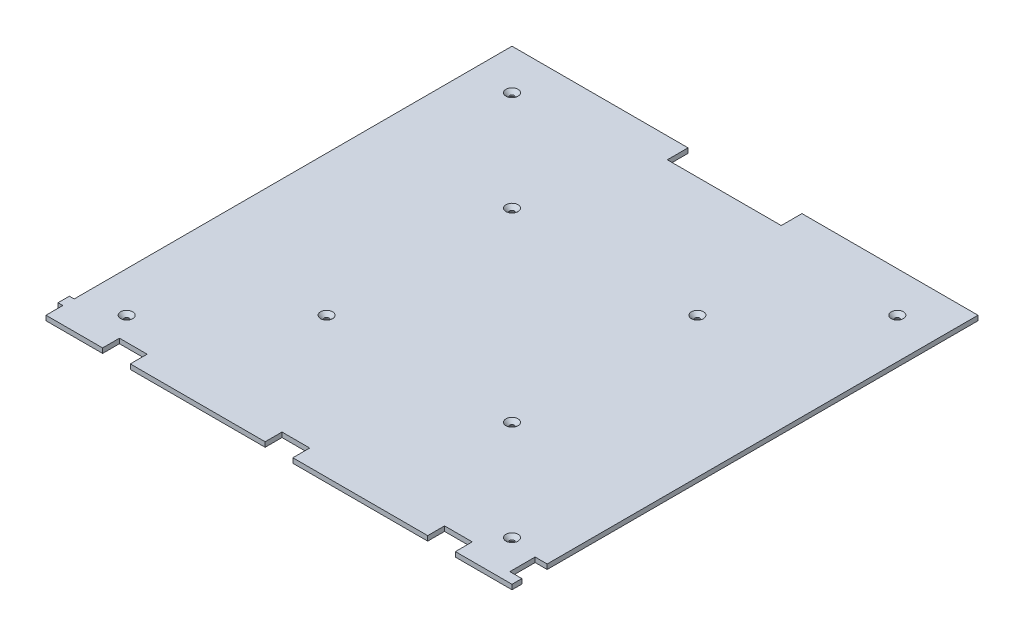
SolidWorks part; units mm, degrees
ref_plane "Front Plane" through (0, 0, 0) normal (0, 0, 1) x (1, 0, 0)
ref_plane "Top Plane" through (0, 0, 0) normal (0, 1, 0) x (1, 0, 0)
ref_plane "Right Plane" through (0, 0, 0) normal (1, 0, 0) x (0, 0, -1)
sketch "Sketch1" plane through (0, 0, 0) normal (0, 1, 0) x (1, 0, 0)
  line L0 (5.5, -97) -> (61.9965, -97) construction
  line L1 (5.5, -90.0036) -> (5.5, -97) construction
  line L2 (-5.5, -90.0036) -> (5.5, -90.0036) construction
  line L3 (-5.5, -97) -> (-5.5, -90.0036) construction
  line L4 (-61.9965, -97) -> (-5.5, -97) construction
  line L5 (-61.9965, -90.0036) -> (-61.9965, -97) construction
  line L6 (-72.9965, -90.0036) -> (-61.9965, -90.0036) construction
  line L7 (-72.9965, -97) -> (-72.9965, -90.0036) construction
  line L8 (-97, -97) -> (-72.9965, -97) construction
  line L9 (-97, -90) -> (-97, -97) construction
  line L10 (-99, -90) -> (-97, -90) construction
  line L11 (-99, -84.8) -> (-99, -90) construction
  line L12 (-97, -84.8) -> (-99, -84.8) construction
  line L13 (-97, 97) -> (-97, -84.8) construction
  line L14 (-23.4, 97) -> (-97, 97) construction
  line L15 (-23.4, 88.4) -> (-23.4, 97) construction
  line L16 (23.4, 88.4) -> (-23.4, 88.4) construction
  line L17 (23.4, 97) -> (23.4, 88.4) construction
  line L18 (97, 97) -> (23.4, 97) construction
  line L19 (97, -82.4) -> (97, 97) construction
  line L20 (92, -82.4) -> (97, -82.4) construction
  line L21 (92, -92.4) -> (92, -82.4) construction
  line L22 (97, -92.4) -> (92, -92.4) construction
  line L23 (97, -97) -> (97, -92.4) construction
  line L24 (72.9965, -97) -> (97, -97) construction
  line L25 (72.9965, -90.0036) -> (72.9965, -97) construction
  line L26 (61.9965, -90.0036) -> (72.9965, -90.0036) construction
  line L27 (61.9965, -97) -> (61.9965, -90.0036) construction
  line L28 (5.75, -96.75) -> (61.7465, -96.75)
  line L29 (61.7465, -96.75) -> (61.7465, -89.7536)
  line L30 (61.7465, -89.7536) -> (73.2465, -89.7536)
  line L31 (73.2465, -89.7536) -> (73.2465, -96.75)
  line L32 (73.2465, -96.75) -> (96.75, -96.75)
  line L33 (96.75, -96.75) -> (96.75, -92.65)
  line L34 (96.75, -92.65) -> (91.75, -92.65)
  line L35 (91.75, -92.65) -> (91.75, -82.15)
  line L36 (91.75, -82.15) -> (96.75, -82.15)
  line L37 (96.75, -82.15) -> (96.75, 96.75)
  line L38 (96.75, 96.75) -> (23.65, 96.75)
  line L39 (23.65, 96.75) -> (23.65, 88.15)
  line L40 (23.65, 88.15) -> (-23.65, 88.15)
  line L41 (-23.65, 88.15) -> (-23.65, 96.75)
  line L42 (-23.65, 96.75) -> (-96.75, 96.75)
  line L43 (-96.75, 96.75) -> (-96.75, -85.05)
  line L44 (-96.75, -85.05) -> (-98.75, -85.05)
  line L45 (-98.75, -85.05) -> (-98.75, -89.75)
  line L46 (-98.75, -89.75) -> (-96.75, -89.75)
  line L47 (-96.75, -89.75) -> (-96.75, -96.75)
  line L48 (-96.75, -96.75) -> (-73.2465, -96.75)
  line L49 (-73.2465, -96.75) -> (-73.2465, -89.7536)
  line L50 (-73.2465, -89.7536) -> (-61.7465, -89.7536)
  line L51 (-61.7465, -89.7536) -> (-61.7465, -96.75)
  line L52 (-61.7465, -96.75) -> (-5.75, -96.75)
  line L53 (-5.75, -96.75) -> (-5.75, -89.7536)
  line L54 (-5.75, -89.7536) -> (5.75, -89.7536)
  line L55 (5.75, -89.7536) -> (5.75, -96.75)
  dimension "D1" = 194
  dimension "D2" = 8.6
  dimension "D3" = 194
  dimension "D4" = 73.6
  dimension "D5" = 46.8
  dimension "D6" = 5
  dimension "D7" = 4.6
  dimension "D8" = 10
  dimension "D9" = 6.9964
  dimension "D10" = 24.0035
  dimension "D11" = 11
  dimension "D12" = 56.4965
  dimension "D13" = 56.4965
  dimension "D14" = 7
  dimension "D15" = 2
  dimension "D16" = 5.2
  dimension "D17" = 97
  dimension "D18" = 97
  dimension "D19" = 0.25
extrude "Boss-Extrude1" add sketch "Sketch1" along normal blind 2
sketch "Sketch2" plane through (0, 0, 0) normal (0, -1, 0) x (1, 0, 0)
  circle A0 centre (80, 80) radius 1
  circle A1 centre (-80, 80) radius 1
  circle A2 centre (-38.5, 38.5) radius 1
  circle A3 centre (38.5, 38.5) radius 1
  circle A4 centre (80, -80) radius 1
  circle A5 centre (-80, -80) radius 1
  circle A6 centre (38.5, -38.5) radius 1
  circle A7 centre (-38.5, -38.5) radius 1
  dimension "D1" = 2
  dimension "D2" = 2
  dimension "D3" = 2
  dimension "D4" = 2
  dimension "D5" = 2
  dimension "D6" = 2
  dimension "D7" = 2
  dimension "D8" = 2
extrude "Cut-Extrude1" cut sketch "Sketch2" against normal through all both and the other way through all
chamfer "Chamfer1" distance 1.5 angle 45 8 edges at (80, 2, 79) (-80, 2, 79) (38.5, 2, 37.5) (-38.5, 2, 37.5) (-38.5, 2, -39.5) (80, 2, -81) (38.5, 2, -39.5) (-80, 2, -81)
